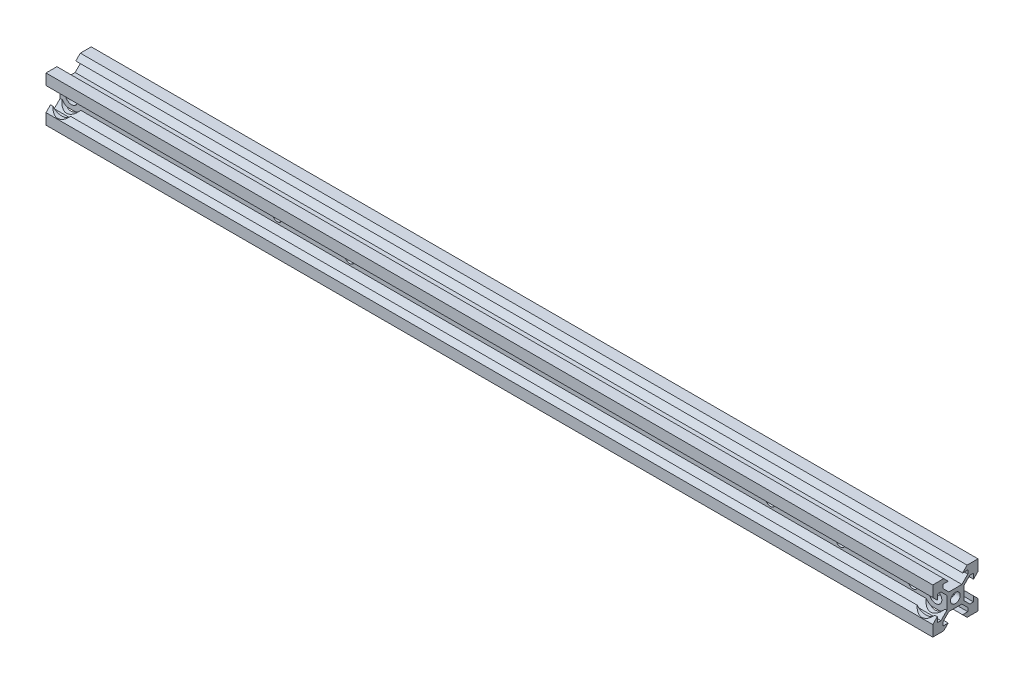
SolidWorks part; units mm, degrees
ref_plane "Front Plane" through (0, 0, 0) normal (0, 0, 1) x (1, 0, 0)
ref_plane "Top Plane" through (0, 0, 0) normal (0, 1, 0) x (1, 0, 0)
ref_plane "Right Plane" through (0, 0, 0) normal (1, 0, 0) x (0, 0, -1)
sketch "Sketch1" plane through (0, 0, 0) normal (0, 0, 1) x (1, 0, 0)
  line L0 (-196, 0) -> (196, 0)
  point P4 (0, 0)
  dimension "D1" = 392
other "20x20-ender - configured 20X20(1)"
ref_plane "Plane1" through (-196, 0, 0) normal (1, 0, 0) x (0, 1, 0)
sketch "Sketch11" plane through (-196, 0, 0) normal (1, 0, 0) x (0, 1, 0)
  line L1 (-10, 10) -> (-5.175, 10)
  line L2 (-10, 10) -> (-10, 5.175)
  line L3 (-10, -10) -> (-5.175, -10)
  line L4 (10, 10) -> (10, 5.175)
  line L7 (-8, 5.5) -> (-6.3839, 5.5)
  line L8 (-8, 5.5) -> (-8, 3.175)
  line L9 (-8, -5.5) -> (-6.3839, -5.5)
  line L10 (8, 5.5) -> (8, 3.175)
  line L11 (2.8661, -3.75) -> (5.5, -6.3839)
  line L12 (3.75, 2.8661) -> (6.3839, 5.5)
  line L13 (-5.5, 8) -> (-3.175, 8)
  line L14 (-5.5, 8) -> (-5.5, 6.3839)
  line L15 (-5.5, -8) -> (-3.175, -8)
  line L16 (5.5, 8) -> (5.5, 6.3839)
  line L17 (-6.3839, 5.5) -> (-3.75, 2.8661)
  line L18 (-3.75, -2.8661) -> (-6.3839, -5.5)
  line L19 (-2.8661, 3.75) -> (2.8661, 3.75)
  line L20 (-3.75, 2.8661) -> (-3.75, -2.8661)
  line L21 (-2.8661, -3.75) -> (2.8661, -3.75)
  line L22 (3.75, 2.8661) -> (3.75, -2.8661)
  line L23 (3.75, -2.8661) -> (6.3839, -5.5)
  line L24 (2.8661, 3.75) -> (5.5, 6.3839)
  line L25 (3.175, 8) -> (5.175, 10)
  line L26 (-3.175, 8) -> (-5.175, 10)
  line L27 (8, 3.175) -> (10, 5.175)
  line L28 (8, -3.175) -> (10, -5.175)
  line L29 (3.175, -8) -> (5.175, -10)
  line L30 (-3.175, -8) -> (-5.175, -10)
  line L31 (-8, -3.175) -> (-10, -5.175)
  line L32 (-8, 3.175) -> (-10, 5.175)
  line L33 (6.3839, 5.5) -> (8, 5.5)
  line L34 (5.5, -6.3839) -> (5.5, -8)
  line L35 (6.3839, -5.5) -> (8, -5.5)
  line L36 (-5.5, -6.3839) -> (-5.5, -8)
  line L37 (5.175, 10) -> (10, 10)
  line L38 (3.175, 8) -> (5.5, 8)
  line L39 (10, -5.175) -> (10, -10)
  line L40 (8, -3.175) -> (8, -5.5)
  line L41 (3.175, -8) -> (5.5, -8)
  line L42 (5.175, -10) -> (10, -10)
  line L43 (-10, -5.175) -> (-10, -10)
  line L44 (-8, -3.175) -> (-8, -5.5)
  line L45 (-5.5, 6.3839) -> (-2.8661, 3.75)
  line L46 (-2.8661, -3.75) -> (-5.5, -6.3839)
  line L55 (-5.175, 10) -> (5.175, 10) construction
  line L56 (10, 5.175) -> (10, -5.175) construction
  line L57 (-5.175, -10) -> (5.175, -10) construction
  line L59 (-10, 5.175) -> (-10, -5.175) construction
  circle A0 centre (0, 0) radius 2.15
  point P0 (0, 0)
  point P5 (0, 0)
  point P6 (0, 0)
  point P11 (0, 0)
  point P16 (0, 0)
  point P44 (0, 0)
  point P60 (0, 10)
  point P63 (0, 0)
  point P64 (0, -10)
  point P65 (10, 0)
  point P80 (-10, 0)
  point P82 (10, 10)
  point P83 (-10, 10)
  point P84 (-10, -10)
  point P85 (10, -10)
hole_wizard "M5x0.8 Tapped Hole1" positions "Sketch12" profile "Sketch14" tap size "M5x0.8" standard "ANSI Metric" end condition through all
sketch "Sketch12" plane through (0, 0, 3.75) normal (0, 0, 1) x (1, 0, 0)
  point P0 (181, 0)
  point P3 (149, 0)
  point P6 (-100, 0)
  point P9 (-68, 0)
sketch "Sketch14" plane through (181, 0, 3.75) normal (1, 0, 0) x (0, -1, 0)
  line L0 (0, 0) -> (0, 13.75)
  line L1 (0, 13.75) -> (2.1, 13.75)
  line L2 (2.1, 13.75) -> (2.1, 0)
  line L5 (2.1, 0) -> (0, 0)
  line L11 (0, -6.35) -> (0, 107.95) construction
  dimension "Thru Tap Drill Dia." = 4.2
  dimension "Thru Tap Drill Depth" = 13.75
cosmetic thread "Hole Thread2"
cosmetic thread "Hole Thread3"
cosmetic thread "Hole Thread9"
cosmetic thread "Hole Thread10"
hole_wizard "CBORE for M5 SHCS1" positions "Sketch17" profile "Sketch18" counterbore size "M5" standard "ANSI Metric" end condition through all
sketch "Sketch17" plane through (0, 0, 10) normal (0, 0, 1) x (1, 0, 0)
  line L0 (196, 0) -> (191, 0) construction
  line L1 (196, 2.8661) -> (196, -2.8661) construction
  line L2 (-196, 0) -> (-191, 0) construction
  line L3 (-196, 2.8661) -> (-196, -2.8661) construction
  point P2 (191, 0)
  point P15 (-191, 0)
  dimension "D1" = 5
sketch "Sketch18" plane through (-191, 0, 10) normal (1, 0, 0) x (0, -1, 0)
  line L0 (0, 0) -> (0, 20)
  line L1 (0, 20) -> (2.75, 20)
  line L3 (2.75, 20) -> (2.75, 6.25)
  line L4 (2.75, 6.25) -> (5, 6.25)
  line L5 (5, 6.25) -> (5, 0)
  line L7 (5, 0) -> (0, 0)
  line L11 (0, -6.35) -> (0, 107.95) construction
  dimension "Thru Hole Dia." = 5.5
  dimension "Thru Hole Depth" = 20
  dimension "C'Bore Dia." = 10
  dimension "C'Bore Depth" = 6.25
hole_wizard "M5x0.8 Tapped Hole2" positions "Sketch21" profile "Sketch22" tap size "M5x0.8" standard "ANSI Metric" end condition through all
sketch "Sketch21" plane through (0, 0, 3.75) normal (0, 0, 1) x (1, 0, 0)
  line L0 (196, 0) -> (118, 0) construction
  line L1 (196, 2.8661) -> (196, -2.8661) construction
  point P0 (118, 0)
  dimension "D1" = 78
sketch "Sketch22" plane through (118, 0, 3.75) normal (1, 0, 0) x (0, -1, 0)
  line L0 (0, 0) -> (0, 13.75)
  line L1 (0, 13.75) -> (2.1, 13.75)
  line L2 (2.1, 13.75) -> (2.1, 0)
  line L5 (2.1, 0) -> (0, 0)
  line L11 (0, -6.35) -> (0, 107.95) construction
  dimension "Thru Tap Drill Dia." = 4.2
  dimension "Thru Tap Drill Depth" = 13.75
cosmetic thread "Hole Thread6" parameters "D2"=5
hole_wizard "M4x0.7 Tapped Hole1" [suppressed] positions "Sketch23" profile "Sketch24" tap size "M4x0.7" standard "ANSI Metric"
sketch "Sketch23" plane through (0, 3.75, 0) normal (0, 1, 0) x (1, 0, 0)
  point P0 (-15, 0)
  point P3 (15, 0)
sketch "Sketch24" plane through (-15, 3.75, 0) normal (1, 0, 0) x (0, 0, 1)
  line L0 (0, 0) -> (0, 13.75)
  line L1 (0, 13.75) -> (1.65, 13.75)
  line L2 (1.65, 13.75) -> (1.65, 0)
  line L5 (1.65, 0) -> (0, 0)
  line L11 (0, -6.35) -> (0, 107.95) construction
  dimension "Thru Tap Drill Dia." = 3.3
  dimension "Thru Tap Drill Depth" = 13.75
cosmetic thread "Hole Thread7" [suppressed] parameters "D2"=4
cosmetic thread "Hole Thread8" [suppressed] parameters "D2"=4
